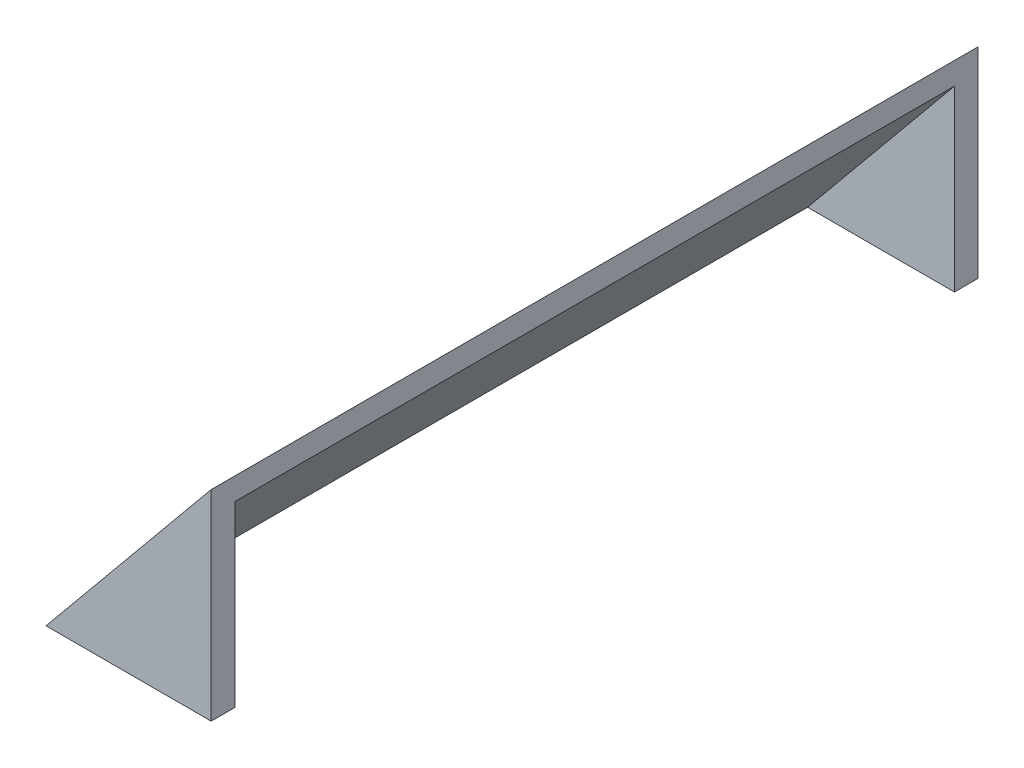
SolidWorks part; units mm, degrees
ref_plane "Front Plane" through (0, 0, 0) normal (0, 0, 1) x (1, 0, 0)
ref_plane "Top Plane" through (0, 0, 0) normal (0, 1, 0) x (1, 0, 0)
ref_plane "Right Plane" through (0, 0, 0) normal (1, 0, 0) x (0, 0, -1)
sketch "Sketch1" plane through (0, 0, 0) normal (0, 0, 1) x (1, 0, 0)
  line L0 (0, 0) -> (0, -17)
  line L1 (0, -17) -> (-14, -17)
  line L2 (-14, -17) -> (0, 0)
  dimension "D1" = 14
  dimension "D2" = 17
extrude "Boss-Extrude2" add sketch "Sketch1" along normal blind 2
sketch "Sketch5" plane through (0, 0, 2) normal (0, 0, 1) x (1, 0, 0)
  line L0 (-14, -17) -> (-12.4455, -17)
  line L1 (-14, -17) -> (0, -17) construction
  line L2 (-12.4455, -17) -> (0, -1.8877)
  line L3 (0, -17) -> (0, 0) construction
  line L4 (0, -1.8877) -> (0, 0)
  line L5 (0, 0) -> (-14, -17)
  dimension "D1" = 1.2
extrude "Boss-Extrude3" add sketch "Sketch5" along normal blind 61
sketch "Sketch6" plane through (0, 0, 63) normal (0, 0, 1) x (1, 0, 0)
  line L0 (0, 0) -> (0, -17)
  line L1 (0, -17) -> (-14, -17)
  line L2 (-14, -17) -> (0, 0)
extrude "Boss-Extrude4" add sketch "Sketch6" along normal blind 2
